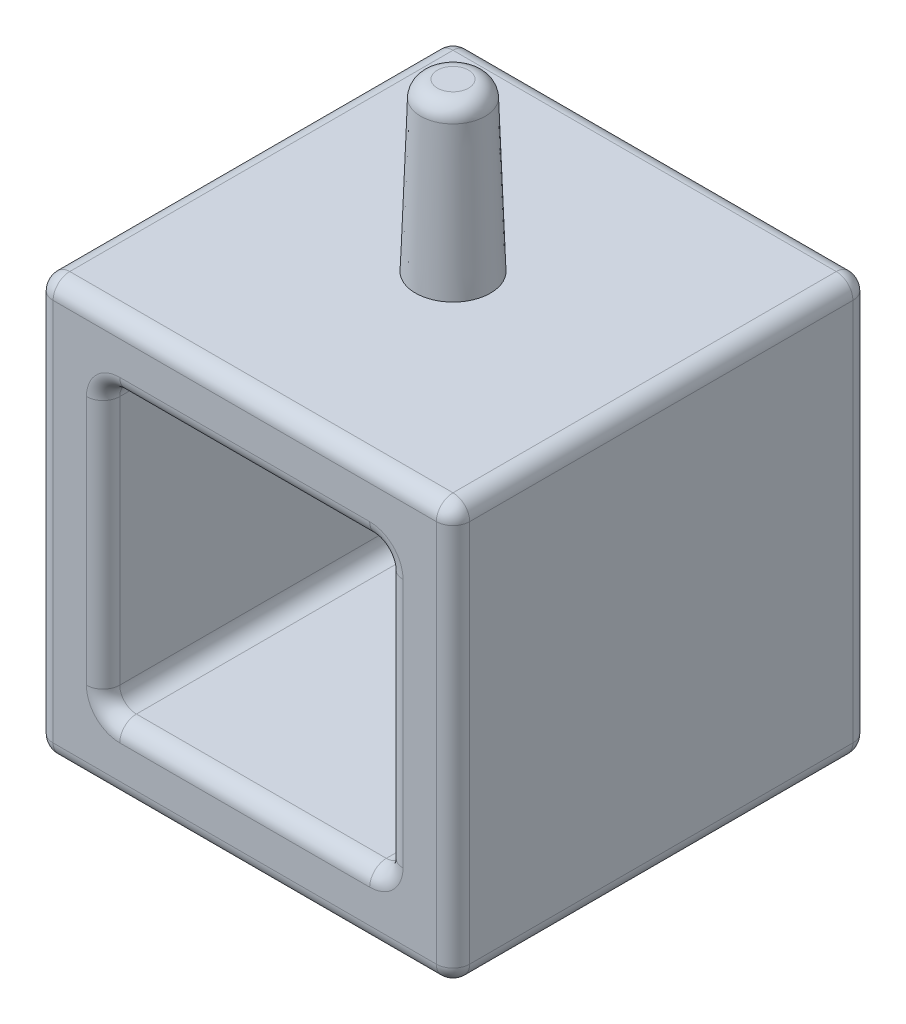
SolidWorks part; units mm, degrees
ref_plane "Front Plane" through (0, 0, 0) normal (0, 0, 1) x (1, 0, 0)
ref_plane "Top Plane" through (0, 0, 0) normal (0, 1, 0) x (1, 0, 0)
ref_plane "Right Plane" through (0, 0, 0) normal (1, 0, 0) x (0, 0, -1)
sketch "Sketch1" plane through (0, 0, 0) normal (0, 0, 1) x (1, 0, 0)
  line L1 (-12.5, -12.5) -> (12.5, -12.5)
  line L2 (-12.5, -12.5) -> (-12.5, 12.5)
  line L3 (-12.5, 12.5) -> (12.5, 12.5)
  line L4 (12.5, -12.5) -> (12.5, 12.5)
  line L5 (-12.5, -12.5) -> (12.5, 12.5) construction
  line L6 (-12.5, 12.5) -> (12.5, -12.5) construction
  point P0 (0, 0)
  dimension "D1" = 25
  dimension "D2" = 25
extrude "Boss-Extrude1" add sketch "Sketch1" along normal blind 25
sketch "Sketch2" plane through (-12.5, 0, 0) normal (-1, 0, 0) x (0, 0, 1)
  line L0 (8.4763, 9.8166) -> (18.5383, 10.0158)
sketch "Sketch3" plane through (-12.5, 0, 0) normal (-1, 0, 0) x (0, 0, 1)
  circle A0 centre (12.5, 0) radius 2.25
  circle A1 centre (12.5, 0) radius 2.5 construction
  dimension "D1" = 0.25
extrude "Boss-Extrude2" add sketch "Sketch3" along normal blind 10 draft 2
sketch "Sketch4" plane through (0, 12.5, 0) normal (0, 1, 0) x (1, 0, 0)
  circle A0 centre (0, -12.5) radius 2.25
  circle A1 centre (0, -12.5) radius 2.5 construction
  dimension "D1" = 0.25
extrude "Boss-Extrude3" add sketch "Sketch4" along normal blind 10 draft 2
sketch "Sketch5" plane through (0, 0, 0) normal (0, 0, -1) x (-1, 0, 0)
  line L0 (12.5, 12.5) -> (12.5, -12.5) construction
  line L1 (-7.5, -8.5) -> (7.5, -8.5)
  line L2 (-8.5, -7.5) -> (-8.5, 7.5)
  line L3 (-7.5, 8.5) -> (7.5, 8.5)
  line L4 (8.5, -7.5) -> (8.5, 7.5)
  line L5 (-8.5, -8.5) -> (8.5, 8.5) construction
  line L6 (-8.5, 8.5) -> (8.5, -8.5) construction
  line L7 (-12.5, 12.5) -> (12.5, 12.5) construction
  arc A0 (-7.5, -8.5) -> (-8.5, -7.5) centre (-7.5, -7.5) cw
  arc A1 (7.5, -8.5) -> (8.5, -7.5) centre (7.5, -7.5) ccw
  arc A2 (7.5, 8.5) -> (8.5, 7.5) centre (7.5, 7.5) cw
  arc A3 (-8.5, 7.5) -> (-7.5, 8.5) centre (-7.5, 7.5) cw
  point P0 (0, 0)
  dimension "D3" = 1
  dimension "D1" = 4
  dimension "D2" = 4
extrude "Cut-Extrude1" cut sketch "Sketch5" against normal up to surface (25 mm away) up to face at (0, 0, 25)
fillet "Fillet1" radius 1 30 edges at (-12.5, 0, 25) (0, 12.5, 25) (8.2071, 8.2071, 25) (0, 8.5, 25) (-8.2071, 8.2071, 25) (-8.5, 0, 25) (-8.2071, -8.2071, 25) (0, -8.5, 25) (8.2071, -8.2071, 25) (8.5, 0, 25) (-12.5, -12.5, 12.5) (0, -12.5, 25) (12.5, 0, 25) (12.5, 12.5, 12.5) (0, 12.5, 0) (-12.5, 0, 0) (12.5, 0, 0) (0, -8.5, 0) (-8.2071, -8.2071, 0) (-8.5, 0, 0) (-8.2071, 8.2071, 0) (0, 8.5, 0) (8.2071, 8.2071, 0) (8.5, 0, 0) (8.2071, -8.2071, 0) (-12.5, 12.5, 12.5) (-22.5, 0, 14.4008) (0, 22.5, 14.4008) (0, -12.5, 0) (12.5, -12.5, 12.5)
